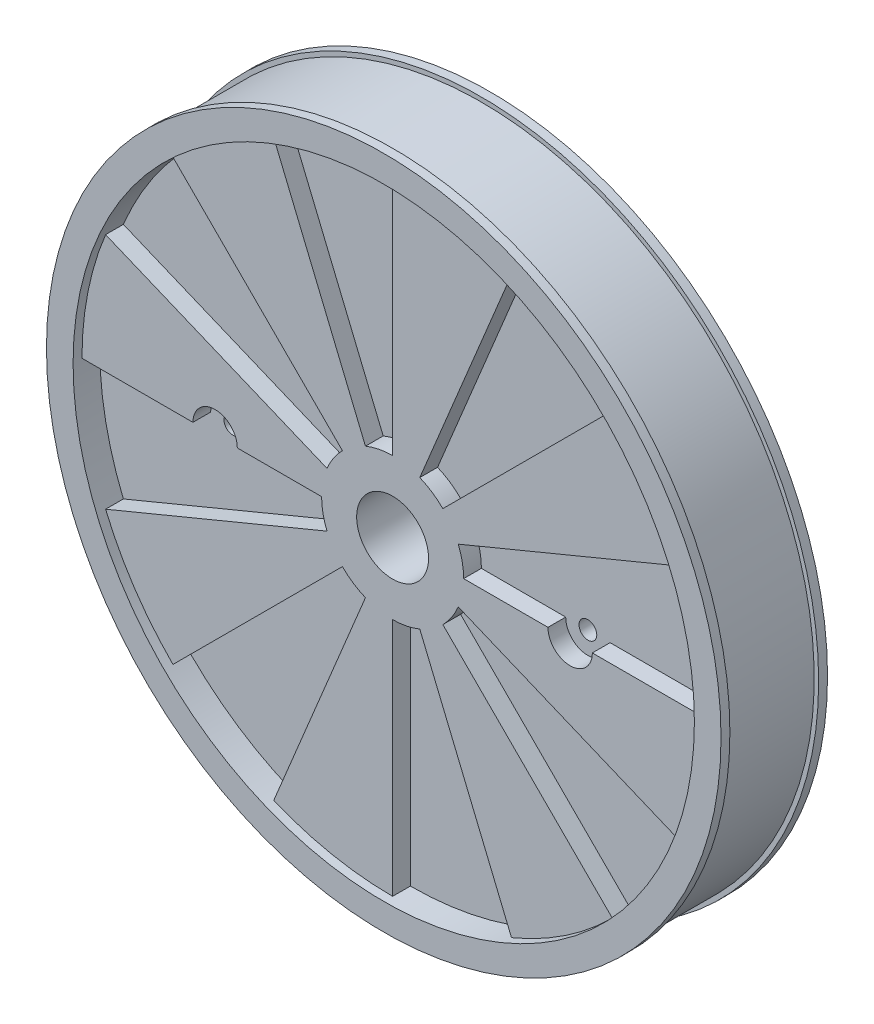
SolidWorks part; units mm, degrees
ref_plane "Alzado" through (0, 0, 0) normal (0, 0, 1) x (1, 0, 0)
ref_plane "Planta" through (0, 0, 0) normal (0, 1, 0) x (1, 0, 0)
ref_plane "Vista lateral" through (0, 0, 0) normal (1, 0, 0) x (0, 0, -1)
sketch "Croquis1" plane through (0, 0, 0) normal (0, 0, 1) x (1, 0, 0)
  circle A0 centre (0, 0) radius 37.5
  dimension "D1" = 75
extrude "Saliente-Extruir1" add sketch "Croquis1" along normal mid plane 7
sketch "Croquis3" plane through (0, 0, 3.5) normal (0, 0, 1) x (1, 0, 0)
  circle A0 centre (0, 0) radius 38
  dimension "D1" = 76
extrude "Saliente-Extruir2" add sketch "Croquis3" along normal blind 1
sketch "Croquis5" plane through (0, 0, -3.5) normal (0, 0, -1) x (-1, 0, 0)
  circle A0 centre (0, 0) radius 38
  dimension "D1" = 76
extrude "Saliente-Extruir4" add sketch "Croquis5" along normal blind 1
sketch "Croquis6" plane through (0, 0, 4.5) normal (0, 0, 1) x (1, 0, 0)
  circle A0 centre (0, 0) radius 4.05
  dimension "D1" = 8.1
extrude "Cortar-Extruir1" cut sketch "Croquis6" against normal blind 31
sketch "Croquis7" plane through (0, 0, 4.5) normal (0, 0, 1) x (1, 0, 0)
  circle A0 centre (0, 0) radius 4.05
  circle A1 centre (0, 0) radius 8
  dimension "D1" = 16
extrude "Saliente-Extruir5" add sketch "Croquis7" along normal blind 2
sketch "Croquis9" plane through (0, 0, 4.5) normal (0, 0, 1) x (1, 0, 0)
  line L0 (0, 35) -> (0, 8)
  line L1 (0, -35) -> (-35, 0) construction
  line L2 (-35, 0) -> (-8, 0)
  line L3 (35, 0) -> (0, 35) construction
  line L4 (0, 35) -> (-35, 0) construction
  line L5 (0, -35) -> (35, 0) construction
  line L6 (-24.7487, 24.7487) -> (-5.6569, 5.6569)
  line L7 (24.7487, 24.7487) -> (5.6569, 5.6569)
  line L8 (-24.7487, -24.7487) -> (0, -35) construction
  line L9 (0, -35) -> (24.7487, -24.7487) construction
  line L10 (24.7487, -24.7487) -> (35, 0) construction
  line L11 (35, 0) -> (24.7487, 24.7487) construction
  line L12 (24.7487, 24.7487) -> (0, 35) construction
  line L13 (0, 35) -> (-24.7487, 24.7487) construction
  line L14 (-24.7487, 24.7487) -> (-35, 0) construction
  line L15 (-35, 0) -> (-24.7487, -24.7487) construction
  line L16 (3.0615, 7.391) -> (13.3939, 32.3358)
  line L17 (-5.6569, -5.6569) -> (-24.7487, -24.7487)
  line L18 (8, 0) -> (35, 0)
  line L19 (0, -8) -> (0, -35)
  line L20 (-3.0615, -7.391) -> (-13.3939, -32.3358)
  line L21 (-3.0615, 7.391) -> (-13.3939, 32.3358)
  line L22 (-7.391, 3.0615) -> (-32.3358, 13.3939)
  line L23 (-7.391, -3.0615) -> (-32.3358, -13.3939)
  line L24 (7.391, 3.0615) -> (32.3358, 13.3939)
  line L25 (7.391, -3.0615) -> (32.3358, -13.3939)
  line L26 (3.0615, -7.391) -> (13.3939, -32.3358)
  line L27 (5.6569, -5.6569) -> (24.7487, -24.7487)
  arc A0 (13.3939, 32.3358) -> (0, 35) centre (0, 0) ccw
  arc A1 (-3.0615, 7.391) -> (-5.6569, 5.6569) centre (0, 0) ccw
  arc A2 (-7.391, 3.0615) -> (-8, 0) centre (0, 0) ccw
  arc A3 (-7.391, -3.0615) -> (-5.6569, -5.6569) centre (0, 0) ccw
  arc A4 (-3.0615, -7.391) -> (0, -8) centre (0, 0) ccw
  arc A5 (3.0615, -7.391) -> (5.6569, -5.6569) centre (0, 0) ccw
  arc A6 (7.391, -3.0615) -> (8, 0) centre (0, 0) ccw
  arc A7 (7.391, 3.0615) -> (5.6569, 5.6569) centre (0, 0) ccw
  arc A8 (3.0615, 7.391) -> (0, 8) centre (0, 0) ccw
  arc A9 (-13.3939, 32.3358) -> (-24.7487, 24.7487) centre (0, 0) ccw
  arc A10 (-32.3358, 13.3939) -> (-35, 0) centre (0, 0) ccw
  arc A11 (-32.3358, -13.3939) -> (-24.7487, -24.7487) centre (0, 0) ccw
  arc A12 (-13.3939, -32.3358) -> (0, -35) centre (0, 0) ccw
  arc A13 (13.3939, -32.3358) -> (24.7487, -24.7487) centre (0, 0) ccw
  arc A14 (32.3358, -13.3939) -> (35, 0) centre (0, 0) ccw
  arc A15 (32.3358, 13.3939) -> (24.7487, 24.7487) centre (0, 0) ccw
extrude "Saliente-Extruir7" add sketch "Croquis9" along normal blind 2
sketch "Croquis10" plane through (0, 0, 4.5) normal (0, 0, 1) x (1, 0, 0)
  circle A0 centre (0, 0) radius 35
  circle A1 centre (0, 0) radius 38
  dimension "D1" = 76
extrude "Saliente-Extruir8" add sketch "Croquis10" along normal blind 3
sketch "Croquis11" plane through (0, 0, 6.5) normal (0, 0, 1) x (1, 0, 0)
  line L0 (0, 0) -> (38, 0) construction
  line L1 (38, 0) -> (-38, 0) construction
  circle A0 centre (0, 0) radius 38 construction
  circle A1 centre (-20, 0) radius 1
  circle A2 centre (20, 0) radius 1
  dimension "D3" = 2
  dimension "D4" = 2
  dimension "D1" = 18
  dimension "D2" = 18
extrude "Cortar-Extruir2" cut sketch "Croquis11" against normal blind 48 and the other way blind 21
sketch "Croquis15" plane through (0, 0, -3.5) normal (0, 0, 1) x (1, 0, 0)
  circle A0 centre (0, 0) radius 37.5
  dimension "D1" = 75
sketch "Croquis17" plane through (0, 0, 6.5) normal (0, 0, 1) x (1, 0, 0)
  line L0 (22.5, 0) -> (21, 0)
  line L1 (-21, 0) -> (-22.5, 0)
  line L2 (19, 0) -> (17.5, 0)
  line L3 (-17.5, 0) -> (-19, 0)
  arc A0 (-19, 0) -> (-21, 0) centre (-20, 0) ccw
  arc A1 (-17.5, 0) -> (-22.5, 0) centre (-20, 0) ccw
  arc A2 (19, 0) -> (21, 0) centre (20, 0) ccw
  arc A3 (17.5, 0) -> (22.5, 0) centre (20, 0) ccw
extrude "Cortar-Extruir6" cut sketch "Croquis15" along normal blind 10 flip side to cut
extrude "Cortar-Extruir10" cut sketch "Croquis17" against normal blind 2
